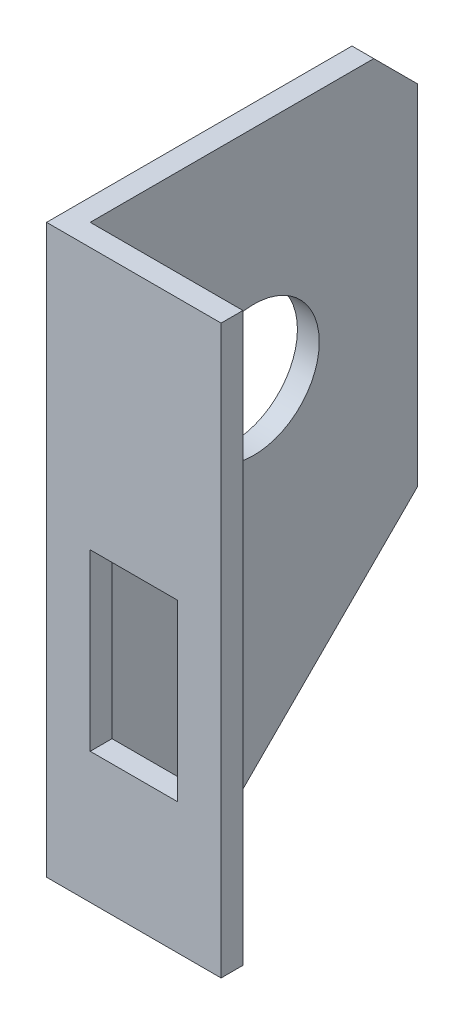
SolidWorks part; units mm, degrees
ref_plane "Front Plane" through (0, 0, 0) normal (0, 0, 1) x (1, 0, 0)
ref_plane "Top Plane" through (0, 0, 0) normal (0, 1, 0) x (1, 0, 0)
ref_plane "Right Plane" through (0, 0, 0) normal (1, 0, 0) x (0, 0, -1)
sketch "Sketch1" plane through (0, 0, 0) normal (0, 1, 0) x (1, 0, 0)
  line L1 (12.7, 1.5875) -> (-12.7, 1.5875)
  line L2 (12.7, 1.5875) -> (12.7, -1.5875)
  line L3 (12.7, -1.5875) -> (-12.7, -1.5875)
  line L4 (-12.7, 1.5875) -> (-12.7, -1.5875)
  line L5 (12.7, 1.5875) -> (-12.7, -1.5875) construction
  line L6 (12.7, -1.5875) -> (-12.7, 1.5875) construction
  line L7 (-9.525, 49.2125) -> (-12.7, 49.2125)
  line L8 (-9.525, 49.2125) -> (-9.525, -1.5875)
  line L9 (-9.525, -1.5875) -> (-12.7, -1.5875)
  line L10 (-12.7, 49.2125) -> (-12.7, -1.5875)
  line L11 (-9.525, 49.2125) -> (-12.7, -1.5875) construction
  line L12 (-9.525, -1.5875) -> (-12.7, 49.2125) construction
  point P0 (0, 0)
  point P6 (-11.1125, 23.8125)
  dimension "D1" = 50.8
  dimension "D2" = 3.175
  dimension "D3" = 3.175
  dimension "D4" = 25.4
extrude "Boss-Extrude1" add sketch "Sketch1" along normal blind 50.8 and the other way blind 31.75 contours L1 L8 L3 L2 | L7 L10 L1 L8 | L8 L1 L4 L3
sketch "Sketch2" plane through (-9.525, 0, 0) normal (1, 0, 0) x (0, 0, -1)
  line L0 (42.8625, 50.8) -> (49.2125, 44.45)
  line L1 (49.2125, 50.8) -> (1.5875, 50.8) construction
  line L2 (49.2125, 50.8) -> (49.2125, -31.75) construction
  line L3 (49.2125, 44.45) -> (49.2125, 50.8)
  line L4 (42.8625, 50.8) -> (49.2125, 50.8)
  line L5 (23.8125, -31.75) -> (49.2125, -31.75)
  line L6 (49.2125, -31.75) -> (1.5875, -31.75) construction
  line L7 (49.2125, -31.75) -> (49.2125, -6.35)
  line L8 (23.8125, -31.75) -> (49.2125, -6.35)
  circle A0 centre (25.4, 19.05) radius 9.525
  dimension "D1" = 19.05
  dimension "D2" = 25.4
  dimension "D3" = 31.75
  dimension "D4" = 25.4
  dimension "D5" = 25.4
  dimension "D6" = 6.35
  dimension "D7" = 6.35
extrude "Cut-Extrude1" cut sketch "Sketch2" against normal up to surface (3.175 mm away) up to face at (-12.7, 9.525, -23.8125)
sketch "Sketch3" plane through (0, 0, 1.5875) normal (0, 0, 1) x (1, 0, 0)
  line L1 (6.35, 12.7) -> (-6.35, 12.7)
  line L2 (6.35, 12.7) -> (6.35, -12.7)
  line L3 (6.35, -12.7) -> (-6.35, -12.7)
  line L4 (-6.35, 12.7) -> (-6.35, -12.7)
  line L5 (6.35, 12.7) -> (-6.35, -12.7) construction
  line L6 (6.35, -12.7) -> (-6.35, 12.7) construction
  point P0 (0, 0)
  dimension "D1" = 25.4
  dimension "D2" = 12.7
extrude "Cut-Extrude2" cut sketch "Sketch3" against normal up to surface (3.175 mm away) up to face at (1.5875, 9.525, -1.5875)
